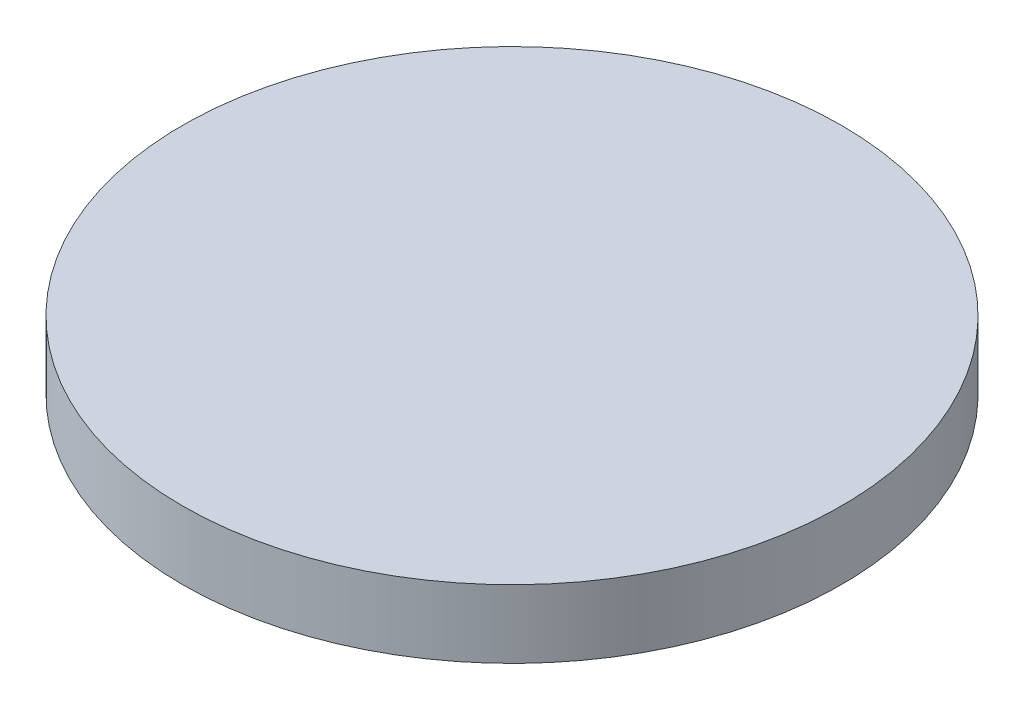
SolidWorks part; units mm, degrees
material "钨"
ref_plane "前视基准面" through (0, 0, 0) normal (0, 0, 1) x (1, 0, 0)
ref_plane "上视基准面" through (0, 0, 0) normal (0, 1, 0) x (1, 0, 0)
ref_plane "右视基准面" through (0, 0, 0) normal (1, 0, 0) x (0, 0, -1)
sketch "草图1" plane through (0, 0, 0) normal (0, 1, 0) x (1, 0, 0)
  circle A0 centre (0, 0) radius 145
  dimension "D1" = 290
extrude "凸台-拉伸1" add sketch "草图1" along normal blind 30
sketch "草图2" plane through (0, 30, 0) normal (0, 1, 0) x (1, 0, 0)
  circle A0 centre (0, 0) radius 38.8 construction
  circle A1 centre (-38.8, 0) radius 7.5
  circle A2 centre (-27.4357, 27.4357) radius 7.5
  circle A3 centre (0, 38.8) radius 7.5
  circle A4 centre (27.4357, 27.4357) radius 7.5
  circle A5 centre (38.8, 0) radius 7.5
  circle A6 centre (27.4357, -27.4357) radius 7.5
  circle A7 centre (0, -38.8) radius 7.5
  circle A8 centre (-27.4357, -27.4357) radius 7.5
  dimension "D1" = 15
  dimension "D2" = 77.6
  dimension "D3" = 8
extrude "切除-拉伸1" [suppressed] cut sketch "草图2" against normal up to next
